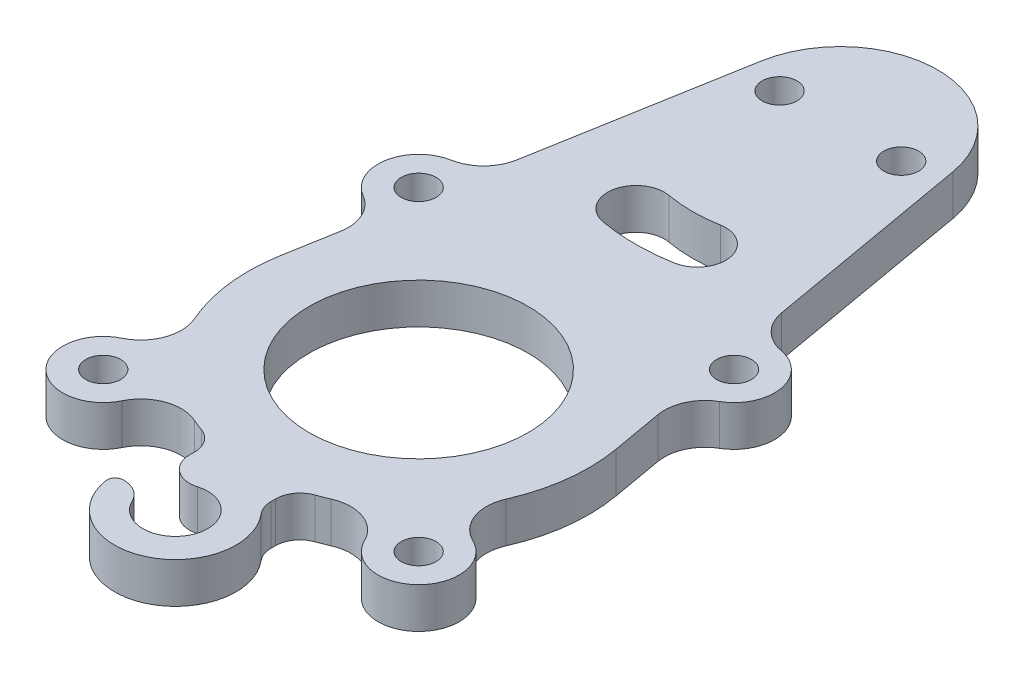
SolidWorks part; units mm, degrees
material "5052-H34"
ref_plane "正面" through (0, 0, 0) normal (0, 0, 1) x (1, 0, 0)
ref_plane "平面" through (0, 0, 0) normal (0, 1, 0) x (1, 0, 0)
ref_plane "右側面" through (0, 0, 0) normal (1, 0, 0) x (0, 0, -1)
sketch "ｽｹｯﾁ1" plane through (0, 0, 0) normal (0, 1, 0) x (1, 0, 0)
  line L0 (0, 0) -> (0, -52) construction
  line L1 (-11.8189, 2.0769) -> (-16.3284, -23.5847)
  line L2 (11.8189, 2.0769) -> (16.3284, -23.5847)
  line L3 (0, 0) -> (-7.5, 0) construction
  line L4 (0, -52) -> (13.5, -52) construction
  line L5 (19.4454, -32.5546) -> (0, -52) construction
  line L6 (19.5732, -42.0498) -> (20.6831, -48.3654)
  line L7 (-19.5732, -42.0498) -> (-20.6831, -48.3654)
  line L8 (19.4454, -71.4454) -> (0, -52) construction
  line L9 (-3.7768, -21.4196) -> (0, 0) construction
  line L10 (-5, -72.3961) -> (-5, -76.4098)
  line L11 (5, -72.3961) -> (5, -76.4098)
  line L12 (-4, -82) -> (-7.5, -82) construction
  line L13 (-5, -76.4098) -> (-2.6667, -79.0186)
  line L14 (-4, -82) -> (-7.5, -82)
  line L15 (-2.6667, -79.0186) -> (0, -82) construction
  line L16 (0, -82) -> (-4, -82) construction
  line L17 (0, -82) -> (-4, -82) construction
  arc A0 (11.8189, 2.0769) -> (-11.8189, 2.0769) centre (0, 0) ccw
  arc A1 (-20.6831, -48.3654) -> (-19.23, -60.4384) centre (0, -52) ccw
  circle A2 centre (-7.5, 0) radius 2.15
  circle A3 centre (7.5, 0) radius 2.15
  circle A4 centre (0, -52) radius 13.5
  circle A5 centre (19.4454, -32.5546) radius 2.15
  circle A6 centre (19.4454, -71.4454) radius 2.15
  circle A7 centre (-19.4454, -71.4454) radius 2.15
  circle A8 centre (-19.4454, -32.5546) radius 2.15
  arc A11 (21.9716, -36.8695) -> (20.3492, -27.6369) centre (19.4454, -32.5546) ccw
  arc A12 (14.9465, -73.627) -> (21.627, -66.9465) centre (19.4454, -71.4454) ccw
  arc A13 (-21.627, -66.9465) -> (-14.9465, -73.627) centre (-19.4454, -71.4454) ccw
  arc A14 (-20.3492, -27.6369) -> (-21.9716, -36.8695) centre (-19.4454, -32.5546) ccw
  arc A15 (21.9716, -36.8695) -> (19.5732, -42.0498) centre (24.4978, -41.1844) ccw
  arc A16 (20.3492, -27.6369) -> (16.3284, -23.5847) centre (21.2529, -22.7193) cw
  arc A17 (-21.9716, -36.8695) -> (-19.5732, -42.0498) centre (-24.4978, -41.1844) cw
  arc A18 (-20.3492, -27.6369) -> (-16.3284, -23.5847) centre (-21.2529, -22.7193) ccw
  arc A19 (21.627, -66.9465) -> (19.23, -60.4384) centre (23.8086, -62.4475) cw
  arc A20 (14.9465, -73.627) -> (8.4384, -71.23) centre (10.4475, -75.8086) ccw
  arc A21 (-14.9465, -73.627) -> (-8.4384, -71.23) centre (-10.4475, -75.8086) cw
  arc A22 (-21.627, -66.9465) -> (-19.23, -60.4384) centre (-23.8086, -62.4475) ccw
  arc A23 (19.23, -60.4384) -> (20.6831, -48.3654) centre (0, -52) ccw
  arc A24 (-8.4384, -71.23) -> (-5, -72.3961) centre (0, -52) ccw
  arc A25 (3.7768, -21.4196) -> (-3.7768, -21.4196) centre (0, 0) cw construction
  arc A26 (-4.3846, -24.8664) -> (4.3846, -24.8664) centre (0, 0) ccw
  arc A27 (-3.1691, -17.9727) -> (3.1691, -17.9727) centre (0, 0) ccw
  arc A28 (-3.1691, -17.9727) -> (-4.3846, -24.8664) centre (-3.7768, -21.4196) ccw
  arc A29 (4.3846, -24.8664) -> (3.1691, -17.9727) centre (3.7768, -21.4196) ccw
  arc A30 (-7.5, -82) -> (5, -76.4098) centre (0, -82) ccw
  arc A31 (-4, -82) -> (-2.6667, -79.0186) centre (0, -82) ccw
  arc A32 (-5, -72.3961) -> (5, -72.3961) centre (0, -52) ccw construction
  arc A33 (5, -72.3961) -> (8.4384, -71.23) centre (0, -52) ccw
  arc A34 (5, -76.4098) -> (-5, -76.4098) centre (0, -82) ccw construction
  arc A35 (-5, -76.4098) -> (-7.5, -82) centre (0, -82) ccw construction
  arc A36 (-2.6667, -79.0186) -> (-4, -82) centre (0, -82) ccw construction
  point P24 (0, -52)
  point P33 (18.7754, -37.5095)
  point P38 (-18.7754, -37.5095)
  point P44 (0, -21.75)
  dimension "D1" = 24
  dimension "D2" = 42
  dimension "D4" = 4.3
  dimension "D5" = 15
  dimension "D6" = 27
  dimension "D8" = 4.3
  dimension "D11" = 10
  dimension "D12" = 5
  dimension "D13" = 5
  dimension "D7" = 3.5
  dimension "D16" = 15
  dimension "D17" = 8
  dimension "D18" = 30
  dimension "D3" = 52
  dimension "D9" = 27.5
  dimension "D14" = 21.75
  dimension "D15" = 10
  dimension "D19" = 10
  dimension "D10" = 4
extrude "ﾎﾞｽ - 押し出し1" add sketch "ｽｹｯﾁ1" along normal blind 5
fillet "ﾌｨﾚｯﾄ1" radius 3 6 edges at (-4, 2.5, 82) (-2.6667, 2.5, 79.0186) (-5, 2.5, 72.3961) (-5, 2.5, 76.4098) (5, 2.5, 76.4098) (5, 2.5, 72.3961)
fillet "ﾌｨﾚｯﾄ2" radius 1 1 edges at (-7.5, 2.5, 82)
